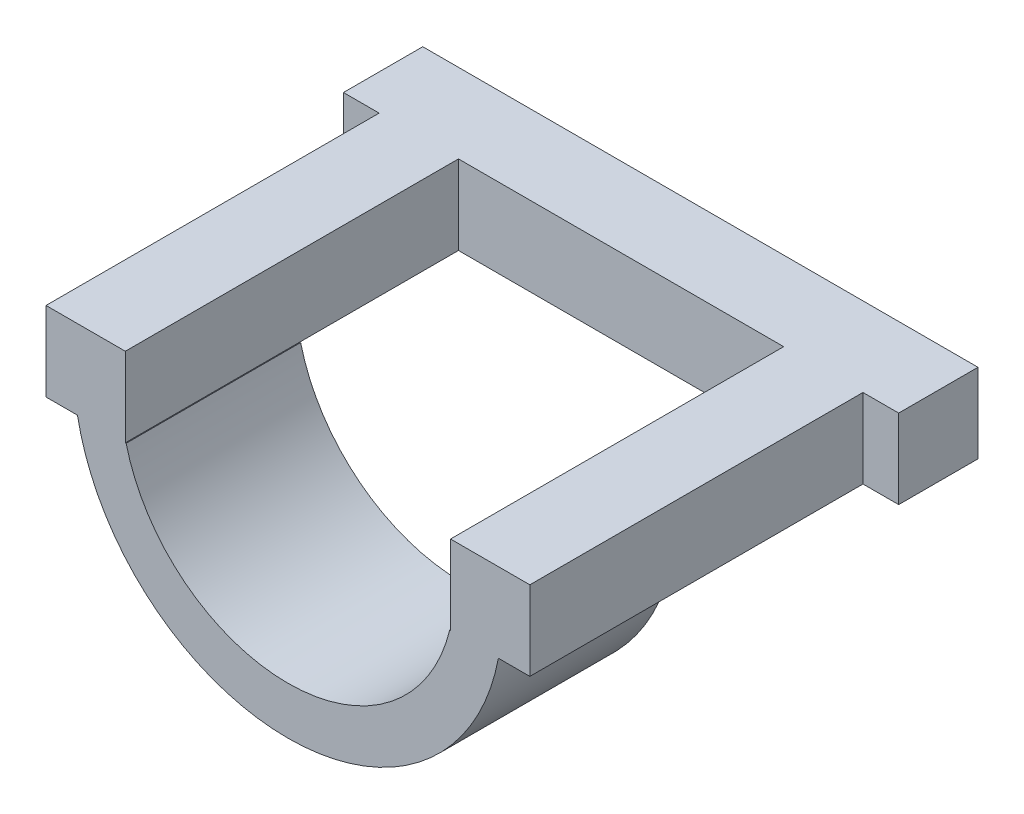
SolidWorks part; units mm, degrees
ref_plane "前视基准面" through (0, 0, 0) normal (0, 0, 1) x (1, 0, 0)
ref_plane "上视基准面" through (0, 0, 0) normal (0, 1, 0) x (1, 0, 0)
ref_plane "右视基准面" through (0, 0, 0) normal (1, 0, 0) x (0, 0, -1)
other "Configuration Table"
sketch "草图1" plane through (0, 0, 0) normal (0, 1, 0) x (1, 0, 0)
  line L1 (0, 0) -> (70, 0)
  line L2 (0, 0) -> (0, 10)
  line L3 (0, 10) -> (70, 10)
  line L4 (70, 0) -> (70, 10)
  dimension "D1" = 10
  dimension "D2" = 70
extrude "凸台-拉伸1" add sketch "草图1" along normal blind 10
sketch "草图2" plane through (0, 0, 0) normal (0, 0, 1) x (1, 0, 0)
  line L0 (0, 10) -> (70, 10) construction
  line L1 (4.5, 10) -> (14.5, 10)
  line L2 (4.5, 10) -> (4.5, 0)
  line L3 (4.5, 0) -> (14.5, 0)
  line L4 (14.5, 10) -> (14.5, 0)
  line L5 (0, 0) -> (70, 0) construction
  line L7 (55.5, 10) -> (65.5, 10)
  line L8 (55.5, 10) -> (55.5, 0)
  line L9 (55.5, 0) -> (65.5, 0)
  line L10 (65.5, 10) -> (65.5, 0)
  point P12 (9.5, 10)
  point P13 (60.5, 10)
  point P14 (35, 10)
  dimension "D1" = 10
  dimension "D2" = 10
  dimension "D3" = 51
  dimension "D4" = 25.5
extrude "凸台-拉伸2" add sketch "草图2" along normal blind 42
sketch "草图3" plane through (0, 0, 42) normal (0, 0, 1) x (1, 0, 0)
  line L0 (14.5, 10) -> (55.5, 10) construction
  line L1 (65.5, 0) -> (65.5, 10) construction
  line L2 (8.467, 0) -> (14.6039, 0)
  line L3 (55.3961, 0) -> (61.533, 0)
  arc A0 (14.6039, 0) -> (55.3961, 0) centre (35, 5) ccw
  arc A1 (8.467, 0) -> (61.533, 0) centre (35, 5) ccw
  point P4 (35, 10)
  point P5 (65.5, 5)
  dimension "D1" = 42
  dimension "D3" = 0
  dimension "D4" = 54
  dimension "D2" = 0
extrude "凸台-拉伸3" add sketch "草图3" against normal blind 22
equation "\"D4@草图2\"=\"D3@草图2\"/2"
